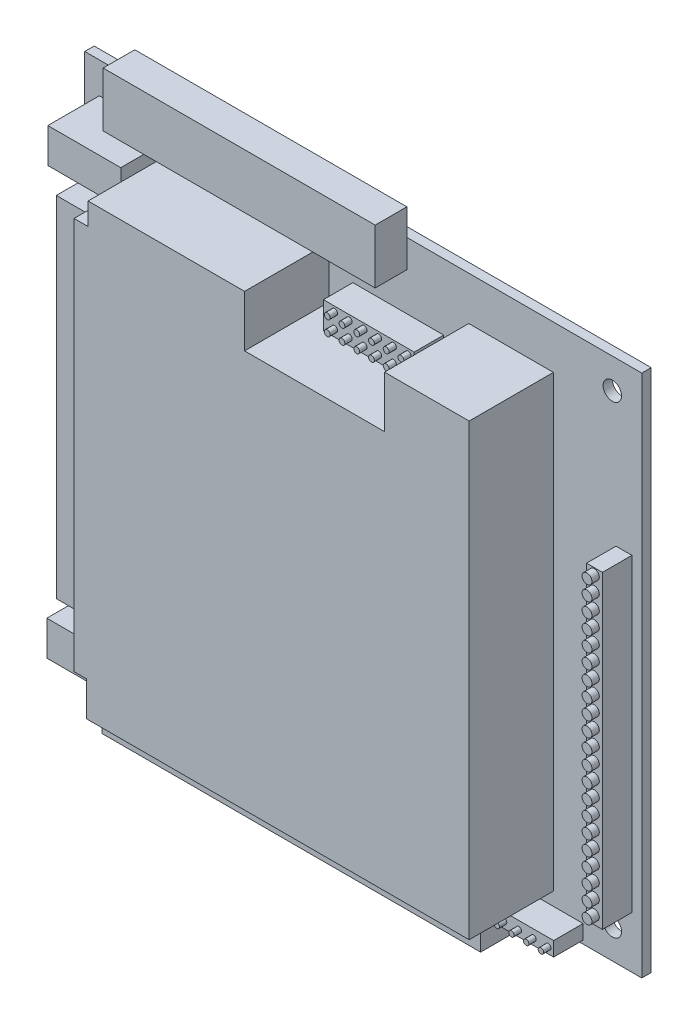
SolidWorks part; units mm, degrees
ref_plane "Front Plane" through (0, 0, 0) normal (0, 0, 1) x (1, 0, 0)
ref_plane "Top Plane" through (0, 0, 0) normal (0, 1, 0) x (1, 0, 0)
ref_plane "Right Plane" through (0, 0, 0) normal (1, 0, 0) x (0, 0, -1)
sketch "Sketch1" plane through (0, 0, 0) normal (0, 0, 1) x (1, 0, 0)
  line L1 (-48.0314, -45.1739) -> (48.0314, -45.1739)
  line L2 (-48.0314, -45.1739) -> (-48.0314, 45.1739)
  line L3 (-48.0314, 45.1739) -> (48.0314, 45.1739)
  line L4 (48.0314, -45.1739) -> (48.0314, 45.1739)
  line L5 (-48.0314, -45.1739) -> (48.0314, 45.1739) construction
  line L6 (-48.0314, 45.1739) -> (48.0314, -45.1739) construction
  point P0 (0, 0)
  dimension "D1" = 96.0628
  dimension "D2" = 90.3478
extrude "PCB" add sketch "Sketch1" along normal blind 1.6256
sketch "Sketch5" plane through (0, 0, 1.6256) normal (0, 0, 1) x (1, 0, 0)
  line L0 (-42.7736, 45.1739) -> (-42.7736, 36.83) construction
  line L1 (48.0314, 45.1739) -> (-48.0314, 45.1739) construction
  line L2 (-42.7736, 36.83) -> (-42.7736, -36.83) construction
  line L3 (-42.7736, -36.83) -> (-42.7736, -45.1739) construction
  line L4 (-48.0314, -45.1739) -> (48.0314, -45.1739) construction
  line L5 (48.0314, -45.1739) -> (48.0314, 45.1739) construction
  line L6 (42.9514, 45.1739) -> (42.9514, 40.005) construction
  line L7 (42.9514, 40.005) -> (42.9514, -40.005) construction
  line L8 (42.9514, -40.005) -> (42.9514, -45.1739) construction
  circle A0 centre (-42.7736, 36.83) radius 1.5875
  circle A1 centre (42.9514, 40.005) radius 1.5875
  circle A2 centre (42.9514, -40.005) radius 1.5875
  circle A3 centre (-42.7736, -36.83) radius 1.5875
  dimension "D5" = 3.175
  dimension "D1" = 73.66
  dimension "D2" = 90.805
  dimension "D3" = 80.01
  dimension "D4" = 5.08
extrude "PCB_Holes" cut sketch "Sketch5" against normal through all
sketch "Sketch2" plane through (0, 0, 1.6256) normal (0, 0, 1) x (1, 0, 0)
  line L0 (-48.0314, 45.1739) -> (-48.0314, -45.1739) construction
  line L1 (-43.6372, 30.5181) -> (-35.6616, 30.5181)
  line L2 (-43.6372, 30.5181) -> (-43.6372, -29.7053)
  line L3 (-43.6372, -29.7053) -> (-35.6616, -29.7053)
  line L4 (-35.6616, 30.5181) -> (-35.6616, -29.7053)
  line L5 (-48.0314, -45.1739) -> (48.0314, -45.1739) construction
  dimension "D1" = 60.2234
  dimension "D2" = 7.9756
  dimension "D3" = 4.3942
  dimension "D4" = 15.4686
extrude "PCI-104_Connector" add sketch "Sketch2" along normal blind 9.2964 and the other way offset from surface (12.6238 mm away) 10.9982 other way up to face at (-41.1861, -36.83, 0)
sketch "Sketch6" plane through (0, 0, 1.6256) normal (0, 0, 1) x (1, 0, 0)
  line L0 (-48.0314, -45.1739) -> (48.0314, -45.1739) construction
  line L1 (-39.5732, -42.3799) -> (25.7048, -42.3799)
  line L2 (-39.5732, -42.3799) -> (-39.5732, -49.7459)
  line L3 (-39.5732, -49.7459) -> (25.7048, -49.7459)
  line L4 (25.7048, -42.3799) -> (25.7048, -49.7459)
  line L5 (-48.0314, 45.1739) -> (-48.0314, -45.1739) construction
  line L6 (48.0314, 45.1739) -> (-48.0314, 45.1739) construction
  line L7 (-39.3954, 40.3479) -> (7.5184, 40.3479)
  line L8 (-39.3954, 40.3479) -> (-39.3954, 49.7459)
  line L9 (-39.3954, 49.7459) -> (7.5184, 49.7459)
  line L10 (7.5184, 40.3479) -> (7.5184, 49.7459)
  dimension "D1" = 7.366
  dimension "D2" = 4.572
  dimension "D3" = 65.278
  dimension "D4" = 8.4582
  dimension "D5" = 9.398
  dimension "D6" = 46.9138
  dimension "D7" = 8.636
  dimension "D8" = 4.572
extrude "PCB_Edge_Conns" add sketch "Sketch6" along normal blind 5.461
sketch "Sketch7" plane through (0, 0, 1.6256) normal (0, 0, 1) x (1, 0, 0)
  line L1 (32.7914, 37.6555) -> (-32.929, 37.6555)
  line L2 (32.7914, 37.6555) -> (32.7914, -39.8145)
  line L3 (32.7914, -39.8145) -> (-45.6811, -39.8145)
  line L4 (-45.6811, -39.8145) -> (-45.6811, -33.8455)
  line L7 (48.0314, -45.1739) -> (48.0314, 45.1739) construction
  line L8 (-45.6811, -33.8455) -> (-35.3477, -33.8455)
  line L9 (-35.3477, -33.8455) -> (-35.3477, 33.8455)
  line L10 (-35.3477, 33.8455) -> (-45.5077, 33.8455)
  line L11 (-45.5077, 33.8455) -> (-45.5077, 39.8145)
  line L12 (-45.5077, 39.8145) -> (-32.929, 39.8145)
  line L13 (-32.929, 39.8145) -> (-32.929, 37.6555)
  line L14 (-42.7736, 36.83) -> (-45.5077, 36.83) construction
  line L15 (-42.7736, -36.83) -> (-45.6811, -36.83) construction
  dimension "D1" = 77.47
  dimension "D2" = 5.969
  dimension "D3" = 10.16
  dimension "D4" = 15.24
extrude "Heat Sink" add sketch "Sketch7" along normal blind 14.5288
sketch "Sketch8" plane through (0, 0, 16.1544) normal (0, 0, 1) x (1, 0, 0)
  line L0 (-45.5077, 39.8145) -> (-45.5077, 33.8455) construction
  line L1 (-45.5077, 39.8145) -> (-32.929, 39.8145)
  line L2 (-45.5077, 39.8145) -> (-45.5077, 33.8455)
  line L3 (-45.5077, 33.8455) -> (-32.929, 33.8455)
  line L4 (-32.929, 39.8145) -> (-32.929, 33.8455)
  line L5 (-45.6811, -39.8145) -> (-33.2121, -39.8145)
  line L6 (-45.6811, -39.8145) -> (-45.6811, -33.8455)
  line L7 (-45.6811, -33.8455) -> (-33.2121, -33.8455)
  line L8 (-33.2121, -39.8145) -> (-33.2121, -33.8455)
extrude "Cut-Extrude1" cut sketch "Sketch8" against normal offset from surface (5.6388 mm away) 8.89 up to face at (-7.6242, -0.3387, 1.6256)
sketch "Sketch9" plane through (0, 0, 16.1544) normal (0, 0, 1) x (1, 0, 0)
  line L0 (32.7914, 37.6555) -> (-32.929, 37.6555) construction
  line L1 (18.1955, 37.6555) -> (-5.9345, 37.6555)
  line L2 (18.1955, 37.6555) -> (18.1955, 28.7655)
  line L3 (18.1955, 28.7655) -> (-5.9345, 28.7655)
  line L4 (-5.9345, 37.6555) -> (-5.9345, 28.7655)
  line L5 (-45.5077, 39.8145) -> (-45.5077, 33.8455) construction
  dimension "D1" = 24.13
  dimension "D2" = 8.89
  dimension "D3" = 39.5732
extrude "Cut-Extrude2" cut sketch "Sketch9" against normal up to surface (14.5288 mm away) up to face at (-7.6242, -0.3387, 1.6256)
sketch "Sketch10" plane through (0, 0, 1.6256) normal (0, 0, 1) x (1, 0, 0)
  line L1 (13.8708, 29.128) -> (-1.7906, 29.128)
  line L2 (13.8708, 29.128) -> (13.8708, 33.7658)
  line L3 (13.8708, 33.7658) -> (-1.7906, 33.7658)
  line L4 (-1.7906, 29.128) -> (-1.7906, 33.7658)
  line L5 (37.9131, -42.0997) -> (27.4563, -42.0997)
  line L6 (37.9131, -42.0997) -> (37.9131, -44.575)
  line L7 (37.9131, -44.575) -> (27.4563, -44.575)
  line L8 (27.4563, -42.0997) -> (27.4563, -44.575)
  line L9 (43.5889, -36.2393) -> (46.3281, -36.2393)
  line L10 (43.5889, -36.2393) -> (43.5889, 17.1007)
  line L11 (43.5889, 17.1007) -> (46.3281, 17.1007)
  line L12 (46.3281, -36.2393) -> (46.3281, 17.1007)
  dimension "D1" = 53.34
extrude "Boss-Extrude1" add sketch "Sketch10" along normal blind 5.08
sketch "Sketch11" plane through (0, 0, 6.7056) normal (0, 0, 1) x (1, 0, 0)
  circle A0 centre (12.8397, 30.3594) radius 0.5045
extrude "Boss-Extrude2" add sketch "Sketch11" along normal blind 1.27
pattern_linear "LPattern1" count 6 spacing 2.54 along (-1, 0, 0) count 2 spacing 2.54 along (0, 1, 0) of "Boss-Extrude2"
sketch "Sketch12" plane through (0, 0, 6.7056) normal (0, 0, 1) x (1, 0, 0)
  circle A0 centre (36.9888, -43.4657) radius 0.4649
extrude "Boss-Extrude3" add sketch "Sketch12" along normal blind 1.27
pattern_linear "LPattern2" count 4 spacing 2.54 along (-1, 0, 0) of "Boss-Extrude3"
sketch "Sketch13" plane through (0, 0, 6.7056) normal (0, 0, 1) x (1, 0, 0)
  circle A0 centre (44.9327, -34.7053) radius 0.8533
extrude "Boss-Extrude4" add sketch "Sketch13" along normal blind 1.27
pattern_linear "LPattern3" count 21 spacing 2.54 along (0, 1, 0) of "Boss-Extrude4"
sketch "Sketch14" plane through (0, 0, 10.5156) normal (0, 0, 1) x (1, 0, 0)
  line L1 (-40.5968, 39.236) -> (-41.0441, 41.5246)
  line L2 (-41.0441, 41.5246) -> (-43.2498, 42.2816)
  line L3 (-43.2498, 42.2816) -> (-45.0081, 40.7499)
  line L4 (-45.0081, 40.7499) -> (-44.5608, 38.4613)
  line L5 (-44.5608, 38.4613) -> (-42.3552, 37.7043)
  line L6 (-42.3552, 37.7043) -> (-40.5968, 39.236)
  line L7 (-40.5968, -41.112) -> (-40.8375, -38.7041)
  line L8 (-40.8375, -38.7041) -> (-43.0432, -37.7086)
  line L9 (-43.0432, -37.7086) -> (-45.0081, -39.1211)
  line L10 (-45.0081, -39.1211) -> (-44.7674, -41.529)
  line L11 (-44.7674, -41.529) -> (-42.5617, -42.5244)
  line L12 (-42.5617, -42.5244) -> (-40.5968, -41.112)
  circle A0 centre (-42.8025, 39.9929) radius 2.0195 construction
  circle A1 centre (-42.8025, -40.1165) radius 2.0957 construction
extrude "Boss-Extrude6" [suppressed] add sketch "Sketch14" along normal blind 6.4516
